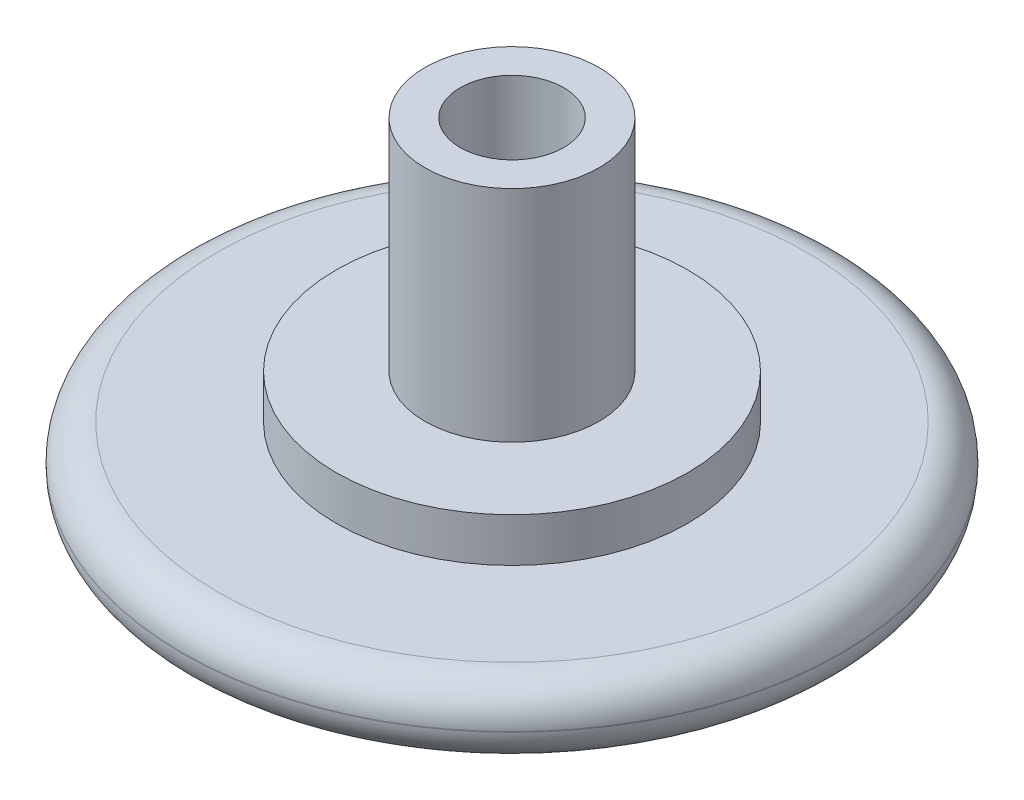
SolidWorks part; units mm, degrees
ref_plane "Alzado" through (0, 0, 0) normal (0, 0, 1) x (1, 0, 0)
ref_plane "Planta" through (0, 0, 0) normal (0, 1, 0) x (1, 0, 0)
ref_plane "Vista lateral" through (0, 0, 0) normal (1, 0, 0) x (0, 0, -1)
ref_axis "Eje1" through (0, 6.93, 0) along (0, -1, 0)
sketch "Croquis1" plane through (0, 0, 0) normal (0, 1, 0) x (1, 0, 0)
  circle A0 centre (0, 0) radius 7.5
extrude "Saliente-Extruir1" add sketch "Croquis1" along normal blind 2
sketch "Croquis2" plane through (0, 2, 0) normal (0, 1, 0) x (1, 0, 0)
  circle A0 centre (0, 0) radius 4
extrude "Saliente-Extruir2" add sketch "Croquis2" along normal blind 1
sketch "Croquis3" plane through (0, 3, 0) normal (0, 1, 0) x (1, 0, 0)
  circle A0 centre (0, 0) radius 1.98
  circle A1 centre (0, 0) radius 1.18
  circle A2 centre (0, 0) radius 1.08 construction
  dimension "D1" = 0.8
  dimension "D2" = 0.1
extrude "Hembra" add sketch "Croquis3" along normal blind 5
sketch "Croquis8" plane through (0, 3, 0) normal (0, 1, 0) x (1, 0, 0)
  circle A0 centre (0, 0) radius 1.98 construction
  circle A1 centre (0, 0) radius 1.18 construction
  circle A2 centre (0, 0) radius 1.08
  dimension "D1" = 0.8
  dimension "D2" = 0.1
extrude "Macho" [suppressed] add sketch "Croquis8" along normal blind 5
sketch "Croquis4" plane through (0, 0, 0) normal (0, 0, 1) x (1, 0, 0)
  line L0 (0, 0) -> (0, 0.6) construction
  line L1 (0, 1) -> (0, 0)
  line L3 (0, 1) -> (3, 1)
  line L4 (0, 0) -> (7.5, 0)
  arc A0 (3, 1) -> (7.5, 0) centre (3, -9.625) cw
revolve "Cortar-Revolución1" cut sketch "Croquis4" angle 360 about axis through (0, 6.93, 0) along (0, -1, 0)
fillet "Redondeo1" radius 0.8 2 edges at (0, 2, 7.5) (0, 0, 7.5)
sketch "Croquis6" plane through (0, 0, 0) normal (0, 0, 1) x (1, 0, 0)
  line L1 (-8.2375, 1.1843) -> (7.9884, 1.1843)
  line L2 (-8.2375, 1.1843) -> (-8.2375, -0.4862)
  line L3 (-8.2375, -0.4862) -> (7.9884, -0.4862)
  line L4 (7.9884, 1.1843) -> (7.9884, -0.4862)
extrude "Cortar-Extruir1" [suppressed] cut sketch "Croquis6" against normal through all both and the other way through all
sketch "Croquis7" plane through (0, 0, 0) normal (0, 0, 1) x (1, 0, 0)
  line L1 (-8.0662, 1.1843) -> (8.658, 1.1843)
  line L2 (-8.0662, 1.1843) -> (-8.0662, 9.1216)
  line L3 (-8.0662, 9.1216) -> (8.658, 9.1216)
  line L4 (8.658, 1.1843) -> (8.658, 9.1216)
extrude "Cortar-Extruir2" [suppressed] cut sketch "Croquis7" against normal through all both and the other way through all
